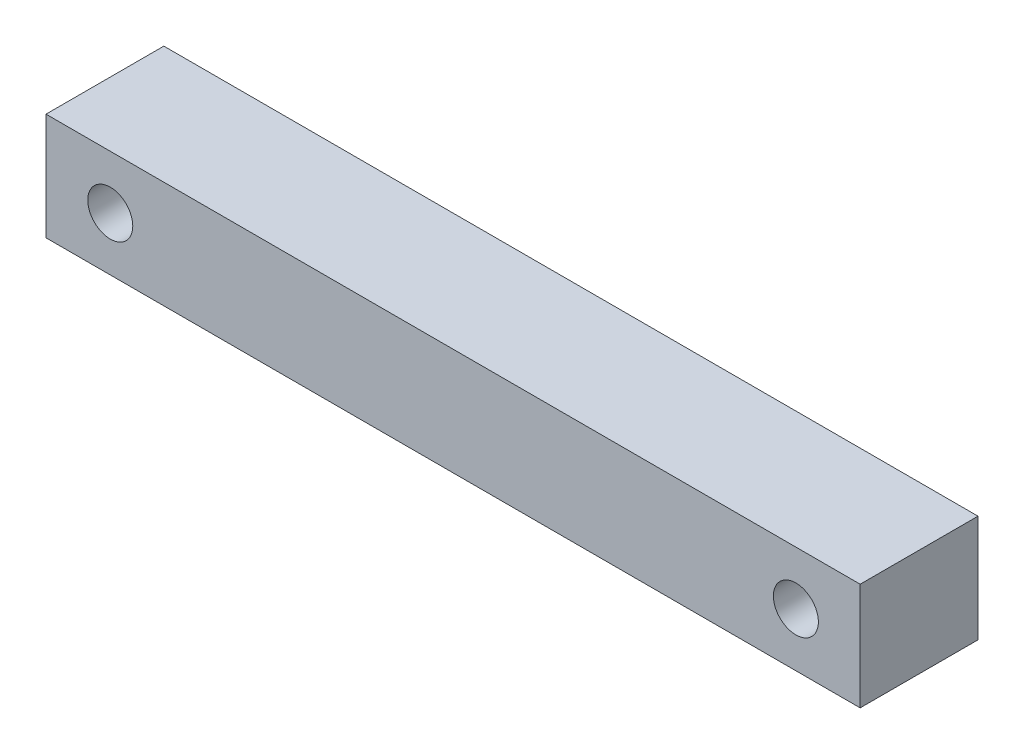
SolidWorks part; units mm, degrees
material "ﾁｰｸ材"
ref_plane "正面" through (0, 0, 0) normal (0, 0, 1) x (1, 0, 0)
ref_plane "平面" through (0, 0, 0) normal (0, 1, 0) x (1, 0, 0)
ref_plane "右側面" through (0, 0, 0) normal (1, 0, 0) x (0, 0, -1)
sketch "ｽｹｯﾁ1" plane through (0, 0, 0) normal (0, 0, 1) x (1, 0, 0)
  line L1 (-19, 2.5) -> (19, 2.5)
  line L2 (-19, 2.5) -> (-19, -2.5)
  line L3 (-19, -2.5) -> (19, -2.5)
  line L4 (19, 2.5) -> (19, -2.5)
  line L5 (-19, 2.5) -> (19, -2.5) construction
  line L6 (-19, -2.5) -> (19, 2.5) construction
  circle A0 centre (-16, 0) radius 1.05
  circle A1 centre (16, 0) radius 1.05
  point P0 (0, 0)
  dimension "D3" = 2.1
  dimension "D4" = 2.1
  dimension "D1" = 5
  dimension "D2" = 38
  dimension "D5" = 16
  dimension "D6" = 16
extrude "ﾎﾞｽ - 押し出し1" add sketch "ｽｹｯﾁ1" along normal blind 5.5
